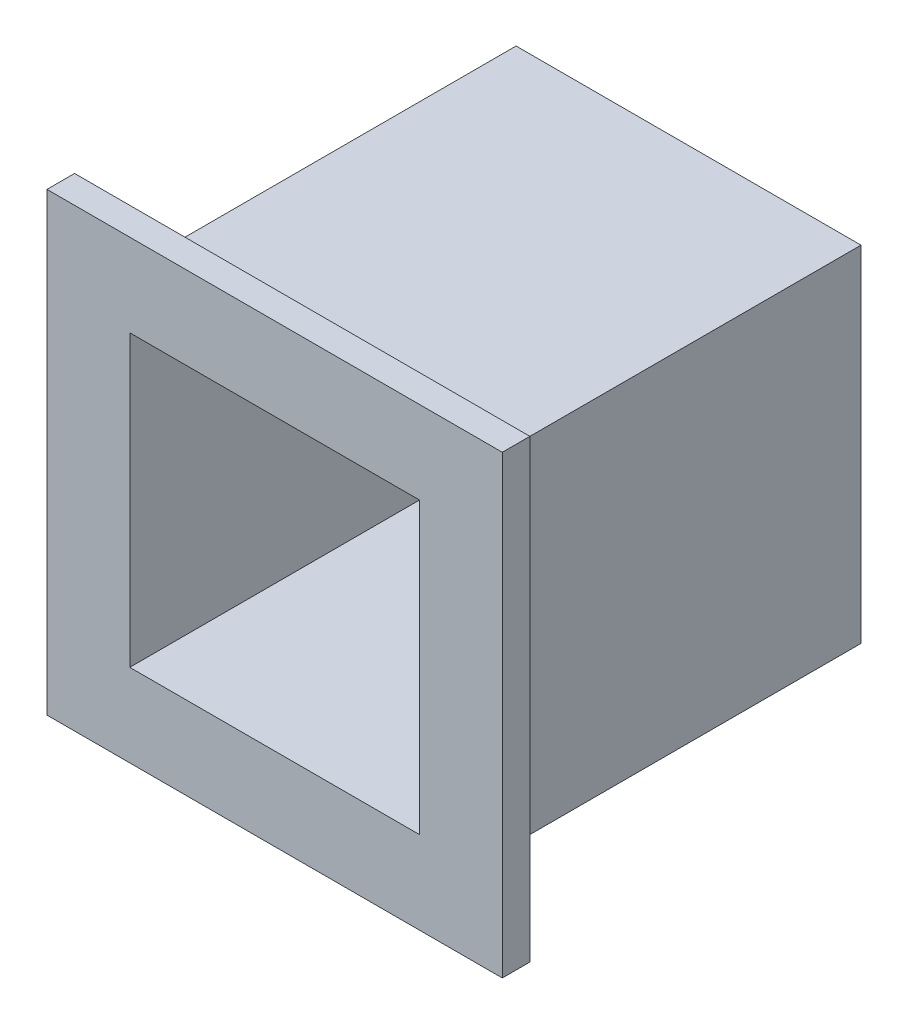
SolidWorks part; units mm, degrees
ref_plane "Front Plane" through (0, 0, 0) normal (0, 0, 1) x (1, 0, 0)
ref_plane "Top Plane" through (0, 0, 0) normal (0, 1, 0) x (1, 0, 0)
ref_plane "Right Plane" through (0, 0, 0) normal (1, 0, 0) x (0, 0, -1)
sketch "Sketch1" plane through (0, 0, 0) normal (0, 0, 1) x (1, 0, 0)
  line L1 (6.25, -6.25) -> (-6.25, -6.25)
  line L2 (6.25, -6.25) -> (6.25, 6.25)
  line L3 (6.25, 6.25) -> (-6.25, 6.25)
  line L4 (-6.25, -6.25) -> (-6.25, 6.25)
  line L5 (6.25, -6.25) -> (-6.25, 6.25) construction
  line L6 (6.25, 6.25) -> (-6.25, -6.25) construction
  point P0 (0, 0)
  dimension "D1" = 12.5
  dimension "D2" = 12.5
extrude "Boss-Extrude1" add sketch "Sketch1" along normal blind 15
shell "Shell3" thickness 1
sketch "Sketch2" plane through (0, 0, 15) normal (0, 0, 1) x (1, 0, 0)
  line L0 (8.25, 8.25) -> (-8.25, 8.25)
  line L1 (-8.25, 8.25) -> (-8.25, -8.25)
  line L2 (-8.25, -8.25) -> (8.25, -8.25)
  line L3 (8.25, -8.25) -> (8.25, 8.25)
  line L4 (-6.25, 6.25) -> (-6.25, -6.25)
  line L5 (-6.25, -6.25) -> (6.25, -6.25)
  line L6 (6.25, -6.25) -> (6.25, 6.25)
  line L7 (6.25, 6.25) -> (-6.25, 6.25)
  line L8 (-6.25, 6.25) -> (-6.25, -6.25)
  line L9 (-6.25, -6.25) -> (6.25, -6.25)
  line L10 (6.25, -6.25) -> (6.25, 6.25)
  line L11 (6.25, 6.25) -> (-6.25, 6.25)
  dimension "D1" = 0
  dimension "D2" = 2
extrude "Boss-Extrude2" add sketch "Sketch2" against normal blind 1
